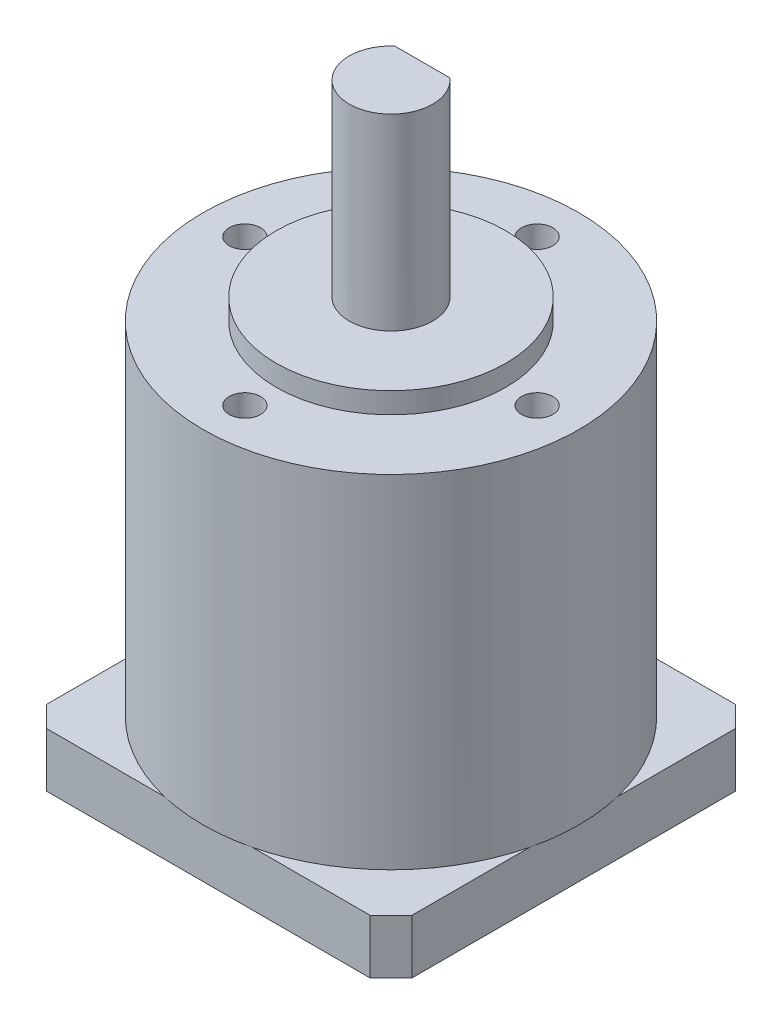
SolidWorks part; units mm, degrees
ref_plane "前视基准面" through (0, 0, 0) normal (0, 0, 1) x (1, 0, 0)
ref_plane "上视基准面" through (0, 0, 0) normal (0, 1, 0) x (1, 0, 0)
ref_plane "右视基准面" through (0, 0, 0) normal (1, 0, 0) x (0, 0, -1)
other "Configuration Table"
sketch "草图1" plane through (0, 0, 0) normal (0, 1, 0) x (1, 0, 0)
  line L1 (-17.5, 17.5) -> (17.5, 17.5)
  line L2 (-17.5, 17.5) -> (-17.5, -17.5)
  line L3 (-17.5, -17.5) -> (17.5, -17.5)
  line L4 (17.5, 17.5) -> (17.5, -17.5)
  line L5 (-17.5, 17.5) -> (17.5, -17.5) construction
  line L6 (-17.5, -17.5) -> (17.5, 17.5) construction
  point P0 (0, 0)
  dimension "D1" = 35
extrude "凸台-拉伸1" add sketch "草图1" along normal blind 5.2
sketch "草图2" plane through (0, 5.2, 0) normal (0, 1, 0) x (1, 0, 0)
  circle A0 centre (0, 0) radius 18
  dimension "D1" = 36
extrude "凸台-拉伸2" add sketch "草图2" along normal blind 32.8
sketch "草图3" plane through (0, 38, 0) normal (0, 1, 0) x (1, 0, 0)
  circle A0 centre (0, 0) radius 11
  dimension "D1" = 22
extrude "凸台-拉伸3" add sketch "草图3" along normal blind 2
sketch "草图4" plane through (0, 40, 0) normal (0, 1, 0) x (1, 0, 0)
  circle A0 centre (0, 0) radius 4
  dimension "D1" = 8
extrude "凸台-拉伸4" add sketch "草图4" along normal blind 18
sketch "草图5" plane through (0, 58, 0) normal (0, 1, 0) x (1, 0, 0)
  line L0 (0, 0) -> (0, 6.8831) construction
  line L2 (5.2734, 10.7663) -> (-5.2734, 10.7663)
  line L3 (5.2734, 10.7663) -> (5.2734, 3)
  line L4 (5.2734, 3) -> (-5.2734, 3)
  line L5 (-5.2734, 10.7663) -> (-5.2734, 3)
  line L6 (5.2734, 10.7663) -> (-5.2734, 3) construction
  line L7 (5.2734, 3) -> (-5.2734, 10.7663) construction
  dimension "D1" = 3
extrude "切除-拉伸1" cut sketch "草图5" against normal blind 15
chamfer "倒角1" distance 2 angle 45 4 edges at (17.5, 2.6, -17.5) (17.5, 2.6, 17.5) (-17.5, 2.6, 17.5) (-17.5, 2.6, -17.5)
sketch "草图6" plane through (0, 38, 0) normal (0, 1, 0) x (1, 0, 0)
  line L0 (0, 0) -> (0, 14) construction
  circle A0 centre (0, 0) radius 14 construction
  circle A1 centre (0, 14) radius 1.5
  circle A2 centre (14, 0) radius 1.5
  circle A3 centre (0, -14) radius 1.5
  circle A4 centre (-14, 0) radius 1.5
  point P14 (0, 0)
  dimension "D1" = 28
  dimension "D2" = 3
  dimension "D3" = 4
extrude "切除-拉伸2" cut sketch "草图6" against normal blind 6
